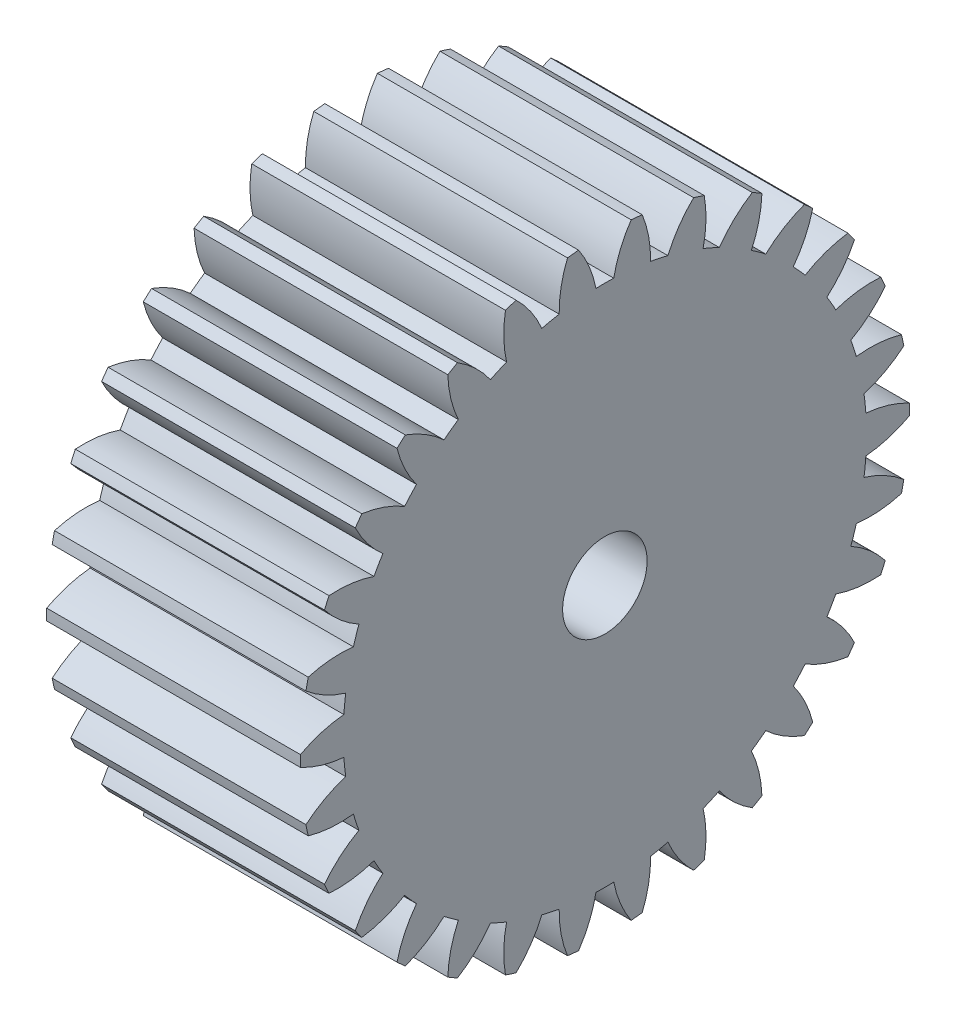
SolidWorks part; units mm, degrees
ref_plane "Plane1" through (0, 0, 0) normal (0, 0, 1) x (1, 0, 0)
ref_plane "Plane2" through (0, 0, 0) normal (0, 1, 0) x (1, 0, 0)
ref_plane "Plane3" through (0, 0, 0) normal (1, 0, 0) x (0, 0, -1)
other "Configuration Table"
sketch "HoldingSke" plane through (0, 0, 0) normal (0, 1, 0) x (1, 0, 0)
  line L0 (0, 0) -> (0.9623, -0.5556)
  line L1 (-15, 0) -> (100, 0) construction
  line L2 (0, 0) -> (-2.1039, 2.3779)
  line L3 (0, 0) -> (-11.863, 4.5341)
  line L4 (0, 0) -> (7.479, 4.318)
  line L5 (0, 0) -> (-46.8476, -17.4728)
  line L6 (0, 0) -> (-9.9476, -6.7116)
  line L7 (-2.1039, 2.3779) -> (8.6586, 51.2059)
  line L8 (-76.2, 54.61) -> (-75.5, 54.61)
  line L9 (-71.009, 38.7566) -> (-53.1078, 45.2721)
  line L10 (-76.2, 71.12) -> (104.1128, 71.12)
  line L11 (0, 0) -> (-12, 0)
  line L12 (-76.2, 101.6) -> (-76.166, 101.6)
  line L13 (24.9733, 27.94) -> (52.9518, 28.4284)
  line L14 (24.9733, 27.94) -> (24.9743, 27.94)
  line L15 (24.9733, 27.94) -> (100.4006, 29.5858)
  line L16 (-63.627, -0.9) -> (-12.827, -0.9)
  circle A0 centre (0, 0) radius 2
  circle A1 centre (0, 0) radius 12.374
  circle A2 centre (0, 0) radius 37.5
  circle A3 centre (0, 0) radius 2
  dimension "MHD" = 24.748
  dimension "Hub_dia" = 75
  dimension "Bore" = 4
  dimension "MBD" = 4
  dimension "Num_teeth" = 30
  dimension "Pitch" = 1.1111
  dimension "Overall_len" = 50
  dimension "Show_teeth" = 30
  dimension "Thickness" = 12
  dimension "OAL" = 50.0001
  dimension "T_dim" = 0.7
  dimension "Ap" = 20
  dimension "H" = 19.05
  dimension "Pitch_radius" = 180.3128
  dimension "Width" = 12
  dimension "Backlash" = 0.034
  dimension "Addendum_fac" = 1
  dimension "Dedendum_fac" = 1.25
  dimension "Clearance_fac" = 0.25
  dimension "Dedendum_add" = 0.001
  dimension "Module" = 0.9
sketch "BasProSke" plane through (0, 0, 0) normal (0, 1, 0) x (1, 0, 0)
  line L0 (-10, 0) -> (60, 0) construction
  line L1 (0, 0) -> (0, 14.4)
  line L2 (0, 0) -> (12, 0)
  line L3 (12, 0) -> (12, 14.4)
  line L4 (12, 14.4) -> (0, 14.4)
  dimension "Thickness" = 12
  dimension "Diameter" = 28.8
revolve "Base-Revolve" add sketch "BasProSke" angle 360 about L0
sketch "TooCutSke" plane through (0, 0, 0) normal (1, 0, 0) x (0, 0, -1)
  line L1 (0, 0) -> (0, 107) construction
  line L2 (0, 0) -> (-0.766, 13.4782) construction
  line L3 (0, 0) -> (-2.819, 26.8212) construction
  line L4 (-0.766, 13.4782) -> (-1.4095, 13.4106) construction
  arc A0 (0.4194, 12.3669) -> (-0.4194, 12.3669) centre (0, 0) ccw
  arc A1 (1.259, 14.3704) -> (-1.259, 14.3704) centre (0, 0) ccw
  circle A2 centre (0, 0) radius 13.5 construction
  circle A3 centre (0, 0) radius 12.6859 construction
  arc A4 (-0.4194, 12.3669) -> (-1.259, 14.3704) centre (-5.7178, 11.3242) ccw
  arc A5 (1.259, 14.3704) -> (0.4194, 12.3669) centre (5.7178, 11.3242) ccw
  dimension "Root_dia" = 24.748
  dimension "Overcut_dia" = 28.8508
  dimension "Pitch_dia" = 27
  dimension "Base_dia" = 25.3717
  dimension "Flank_rad" = 5.4
  dimension "Half_ang" = 6
  dimension "Half_CT" = 0.647
extrude "ToothCut" cut sketch "TooCutSke" along normal through all
fillet "Breaks" [suppressed] radius 0.018
fillet "RootFillets" [suppressed] radius 0.226
pattern_circular "TeethCuts" count 30 every 12 about axis through (-10, 0, 0) along (1, 0, 0) of "ToothCut", "RootFillets", "Breaks"
sketch "HubNeaOneSke" plane through (0, 0, 0) normal (-1, 0, 0) x (0, 0, 1)
  circle A0 centre (0, 0) radius 12.374
  dimension "Diameter" = 24.748
extrude "HubNearOne" [suppressed] add sketch "HubNeaOneSke" along normal blind 38.0001
sketch "HubNeaBotSke" plane through (0, 0, 0) normal (-1, 0, 0) x (0, 0, 1)
  circle A0 centre (0, 0) radius 12.374
  dimension "Diameter" = 24.748
extrude "HubNearBoth" [suppressed] add sketch "HubNeaBotSke" along normal blind 19
ref_plane "FarPln" through (12, 0, 0) normal (1, 0, 0) x (0, 0, -1)
sketch "HubFarSke" plane through (12, 0, 0) normal (1, 0, 0) x (0, 0, -1)
  circle A0 centre (0, 0) radius 12.374
  dimension "Diameter" = 24.748
extrude "HubFar" [suppressed] add sketch "HubFarSke" along normal blind 19
sketch "BorSke" plane through (0, 0, 0) normal (1, 0, 0) x (0, 0, -1)
  circle A0 centre (0, 0) radius 2
  dimension "Diameter" = 4
extrude "Bore" cut sketch "BorSke" along normal mid plane 100.0001
sketch "KeySke" plane through (0, 0, 0) normal (1, 0, 0) x (0, 0, -1)
  line L0 (-0.8, 0) -> (-0.8, 2.7)
  line L1 (-0.8, 2.7) -> (0.8, 2.7)
  line L2 (0.8, 2.7) -> (0.8, 0)
  line L3 (0, 0) -> (0, 34) construction
  line L4 (-0.8, 0) -> (0.8, 0)
  dimension "Offset" = 2.7
  dimension "Width" = 1.6
extrude "Keyway" [suppressed] cut sketch "KeySke" along normal mid plane 100.0001
pattern_circular "Keyway2" [suppressed] count 2 every 90 about axis through (-10, 0, 0) along (1, 0, 0)
equation "' \"Module@HoldingSke\" = 6.35"
equation "' \"Num_teeth@HoldingSke\" = 12"
equation "' \"Ap@HoldingSke\" =  20"
equation "' \"Ap@HoldingSke\" = 20"
equation "' \"Width@HoldingSke\" = 0.5 * 25.4"
equation "' \"Hub_dia@HoldingSke\"= 1 * 25.4"
equation "' \"Hub_dia@HoldingSke\" = 1 * 25.4"
equation "' \"Overall_len@HoldingSke\" = 1.0 * 25.4"
equation "' \"Bore@HoldingSke\" = 0.75 * 25.4"
equation "' \"T_dim@HoldingSke\" = 0.1 * 25.4"
equation "' \"Width@KeySke\" = 0.25 * 25.4"
equation "' \"Show_teeth@HoldingSke\" = 13"
equation "' \"Backlash@HoldingSke\" = 0.009 * 25.4"
equation "' \"Addendum_fac@HoldingSke\" = 1.0"
equation "' \"Dedendum_fac@HoldingSke\" = 1.25"
equation "' \"Dedendum_add@HoldingSke\" = 0.00005 * 25.4"
equation "' \"Clearance_fac@HoldingSke\" = 0.25"
equation "\"Pitch@HoldingSke\" = 1 / \"Module@HoldingSke\""
equation "\"Overcut_dia@TooCutSke\" = (\"Num_teeth@HoldingSke\" + 2 * \"Addendum_fac@HoldingSke\") / \"Pitch@HoldingSke\" + 0.002 * 25.4"
equation "\"Pitch_dia@TooCutSke\" = \"Num_teeth@HoldingSke\" / \"Pitch@HoldingSke\""
equation "\"Base_dia@TooCutSke\" = \"Num_teeth@HoldingSke\" / \"Pitch@HoldingSke\" * cos((\"Ap@HoldingSke\"  * 3.14159265 / 180))"
equation "\"Root_dia@TooCutSke\" = (\"Num_teeth@HoldingSke\" + 2) / \"Pitch@HoldingSke\" - 2 * (\"Addendum_fac@HoldingSke\" + \"Dedendum_fac@HoldingSke\") / \"Pitch@HoldingSke\" - \"Dedendum_add@HoldingSke\" * 2"
equation "\"Half_ang@TooCutSke\" = 180 / \"Num_teeth@HoldingSke\""
equation "\"Half_CT@TooCutSke\" = \"Num_teeth@HoldingSke\" / \"Pitch@HoldingSke\" * sin((3.14159265 / 2 / \"Num_teeth@HoldingSke\")) / 2 - 7 * \"Backlash@HoldingSke\" / 4"
equation "\"Flank_rad@TooCutSke\" = \"Num_teeth@HoldingSke\" / \"Pitch@HoldingSke\" / 5"
equation "\"Radius@RootFillets\" = \"Clearance_fac@HoldingSke\" / \"Pitch@HoldingSke\" + \"Dedendum_add@HoldingSke\""
equation "\"Break_rad@Breaks\" = 0.02 / \"Pitch@HoldingSke\""
equation "\"Thickness@HoldingSke\" = \"Width@HoldingSke\""
equation "\"OAL@HoldingSke\" = \"Thickness@HoldingSke\""
equation "\"MHD@HoldingSke\" = (\"Num_teeth@HoldingSke\" + 2) / \"Pitch@HoldingSke\" - 2 * (\"Addendum_fac@HoldingSke\" + \"Dedendum_fac@HoldingSke\")  / \"Pitch@HoldingSke\" - \"Dedendum_add@HoldingSke\" * 2"
equation "\"MBD@HoldingSke\" = (\"Num_teeth@HoldingSke\" + 2) / \"Pitch@HoldingSke\" - 2 * (\"Addendum_fac@HoldingSke\" + \"Dedendum_fac@HoldingSke\")  / \"Pitch@HoldingSke\" - \"Dedendum_add@HoldingSke\" * 2 - 0.002 * 25.4"
equation "\"MHD@HoldingSke\" = ((sgn( \"MHD@HoldingSke\" - \"Hub_dia@HoldingSke\" )-1)*( \"MHD@HoldingSke\" - \"Hub_dia@HoldingSke\" ))/-2+ \"Hub_dia@HoldingSke\""
equation "\"MBD@HoldingSke\" = ((sgn( \"MBD@HoldingSke\" - \"Bore@HoldingSke\" )-1)*( \"MBD@HoldingSke\" - \"Bore@HoldingSke\" ))/-2+ \"Bore@HoldingSke\""
equation "\"OAL@HoldingSke\" = ((sgn( \"OAL@HoldingSke\" - \"Overall_len@HoldingSke\" )+1)*( \"OAL@HoldingSke\" - \"Overall_len@HoldingSke\" ))/2 + \"Overall_len@HoldingSke\" + 0.000002 * 25.4"
equation "\"Num_teeth@TeethCuts\" = int( \"Show_teeth@HoldingSke\" ) + 1"
equation "\"Num_teeth@TeethCuts\" = ((sgn( \"Num_teeth@TeethCuts\" - \"Num_teeth@HoldingSke\" )-1)*( \"Num_teeth@TeethCuts\" - \"Num_teeth@HoldingSke\" ))/-2+ \"Num_teeth@HoldingSke\""
equation "\"Num_teeth@TeethCuts\" = ((sgn( \"Num_teeth@TeethCuts\" - 2.0)+1)*( \"Num_teeth@TeethCuts\" - 2.0))/2 +2.0"
equation "\"Angle@TeethCuts\" = 360.0 / \"Num_teeth@HoldingSke\""
equation "\"Diameter@BasProSke\" = (\"Num_teeth@HoldingSke\" + 2 * \"Addendum_fac@HoldingSke\") / \"Pitch@HoldingSke\""
equation "\"Thickness@BasProSke\"  = \"Thickness@HoldingSke\""
equation "' \"Fillet_rad@BasProSke\" =  \"Thickness@HoldingSke\" * 0.05"
equation "' \"Fillet_rad@BasProSke\" = \"Thickness@HoldingSke\" * 0.05"
equation "\"MHD@HoldingSke\" = ((sgn( \"MHD@HoldingSke\" - \"Root_dia@TooCutSke\" )-1)*( \"MHD@HoldingSke\" - \"Root_dia@TooCutSke\" ))/-2+ \"Root_dia@TooCutSke\""
equation "\"Diameter@HubNeaOneSke\" = \"MHD@HoldingSke\""
equation "\"Length@HubNearOne\" = \"OAL@HoldingSke\" - \"Thickness@BasProSke\""
equation "\"Diameter@HubNeaBotSke\" = \"MHD@HoldingSke\""
equation "\"Length@HubNearBoth\" = ( \"OAL@HoldingSke\" - \"Thickness@BasProSke\" ) / 2.0"
equation "\"Thickness@FarPln\" = \"Thickness@BasProSke\""
equation "\"Diameter@HubFarSke\" = \"MHD@HoldingSke\""
equation "\"Length@HubFar\" = ( \"OAL@HoldingSke\" - \"Thickness@BasProSke\" ) / 2.0"
equation "\"Diameter@BorSke\" = \"MBD@HoldingSke\""
equation "\"D1@Bore\" = \"OAL@HoldingSke\" * 2.0"
equation "\"D1@Keyway\" = \"OAL@HoldingSke\" * 2.0"
equation "\"Offset@KeySke\" = \"T_dim@HoldingSke\" + \"MBD@HoldingSke\" / 2.0"
